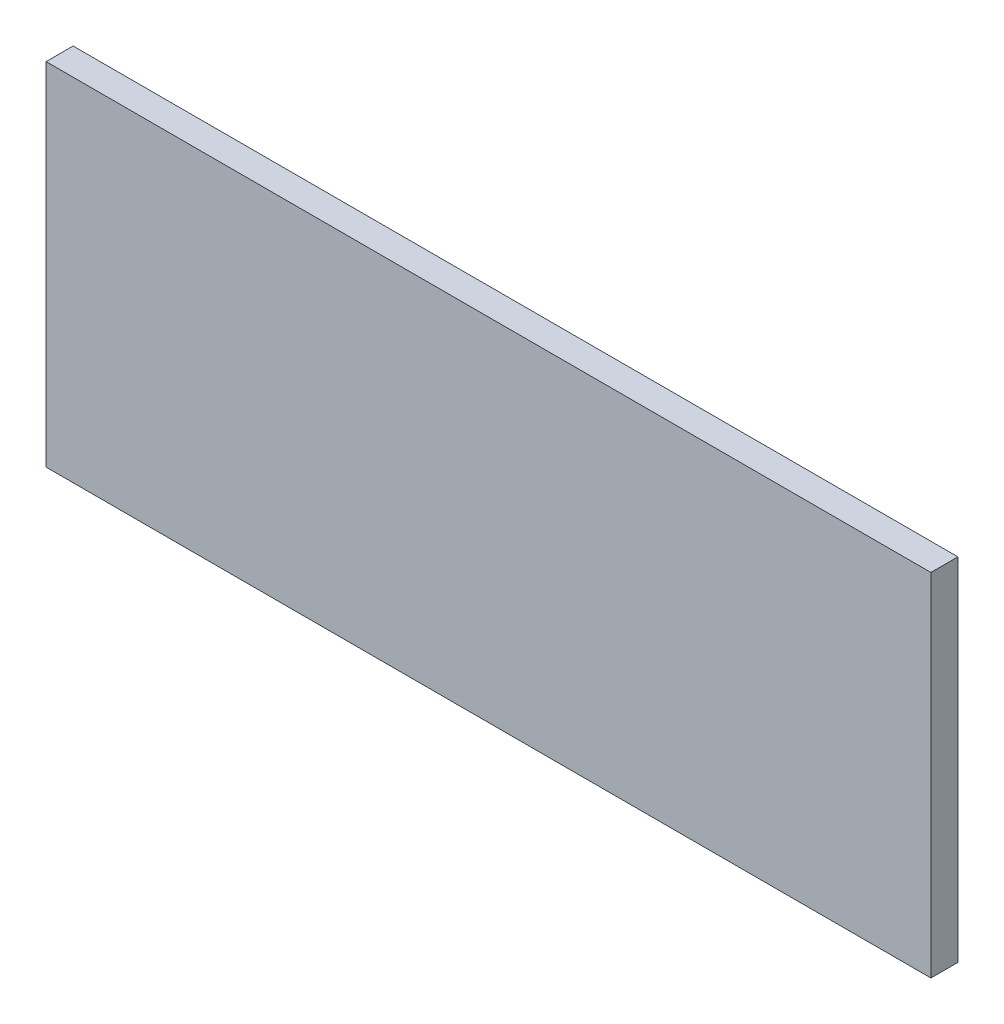
SolidWorks part; units mm, degrees
ref_plane "Alzado" through (0, 0, 0) normal (0, 0, 1) x (1, 0, 0)
ref_plane "Planta" through (0, 0, 0) normal (0, 1, 0) x (1, 0, 0)
ref_plane "Vista lateral" through (0, 0, 0) normal (1, 0, 0) x (0, 0, -1)
sketch "Croquis1" plane through (0, 0, 0) normal (0, 0, 1) x (1, 0, 0)
  line L1 (0, 0) -> (131, 0)
  line L2 (0, 0) -> (0, -52)
  line L3 (0, -52) -> (131, -52)
  line L4 (131, 0) -> (131, -52)
  dimension "D1" = 131
  dimension "D2" = 52
extrude "Saliente-Extruir1" add sketch "Croquis1" along normal blind 4
